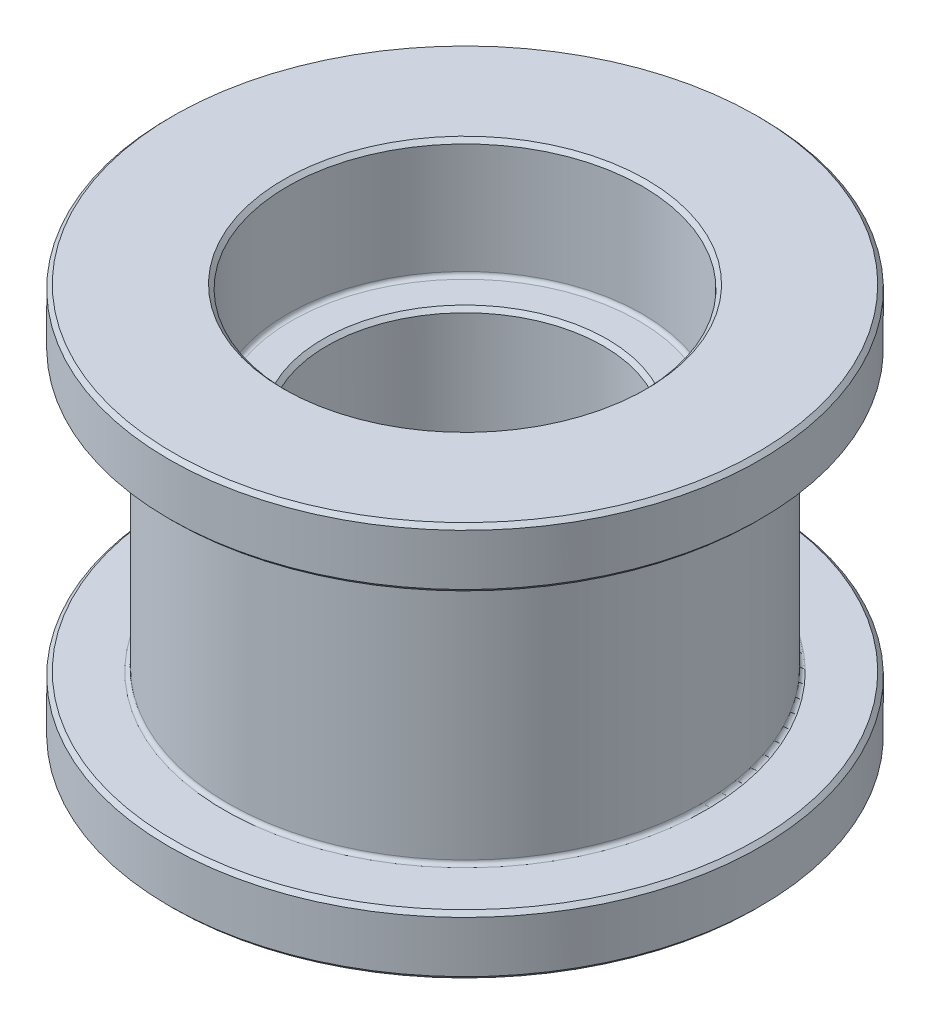
SolidWorks part; units mm, degrees
material "6061-T6 (SS)"
ref_plane "Přední rovina" through (0, 0, 0) normal (0, 0, 1) x (1, 0, 0)
ref_plane "Horní rovina" through (0, 0, 0) normal (0, 1, 0) x (1, 0, 0)
ref_plane "Pravá rovina" through (0, 0, 0) normal (1, 0, 0) x (0, 0, -1)
sketch "Skica1" plane through (0, 0, 0) normal (0, 0, 1) x (1, 0, 0)
  line L0 (4.5, 10) -> (7.5, 10)
  line L1 (7.5, 10) -> (7.5, 8.5)
  line L2 (7.5, 8.5) -> (6, 8.5)
  line L3 (6, 8.5) -> (6, 1.5)
  line L4 (6, 1.5) -> (7.5, 1.5)
  line L5 (7.5, 1.5) -> (7.5, 0)
  line L6 (7.5, 0) -> (4.5, 0)
  line L8 (4.5, 10) -> (4.5, 7)
  line L9 (4.5, 7) -> (3.5, 7)
  line L10 (3.5, 7) -> (3.5, 3)
  line L11 (3.5, 3) -> (4.5, 3)
  line L12 (4.5, 3) -> (4.5, 0)
  line L13 (0, 0) -> (0, -4.1646) construction
  dimension "D1" = 1.5
  dimension "D2" = 7
  dimension "D3" = 4.5
  dimension "D4" = 3.5
  dimension "D5" = 6
  dimension "D6" = 3
  dimension "D7" = 7.5
revolve "Rotovat1" add sketch "Skica1" angle 360 about L13
chamfer "Zkosení1" distance 0.1 angle 45 8 edges at (0, 3, 3.5) (0, 0, 4.5) (0, 7, 3.5) (0, 0, 7.5) (0, 1.5, 7.5) (0, 8.5, 7.5) (0, 10, 7.5) (0, 10, 4.5)
fillet "Zaoblit1" radius 0.1 4 edges at (0, 3, 4.5) (0, 1.5, 6) (0, 8.5, 6) (0, 7, 4.5)
